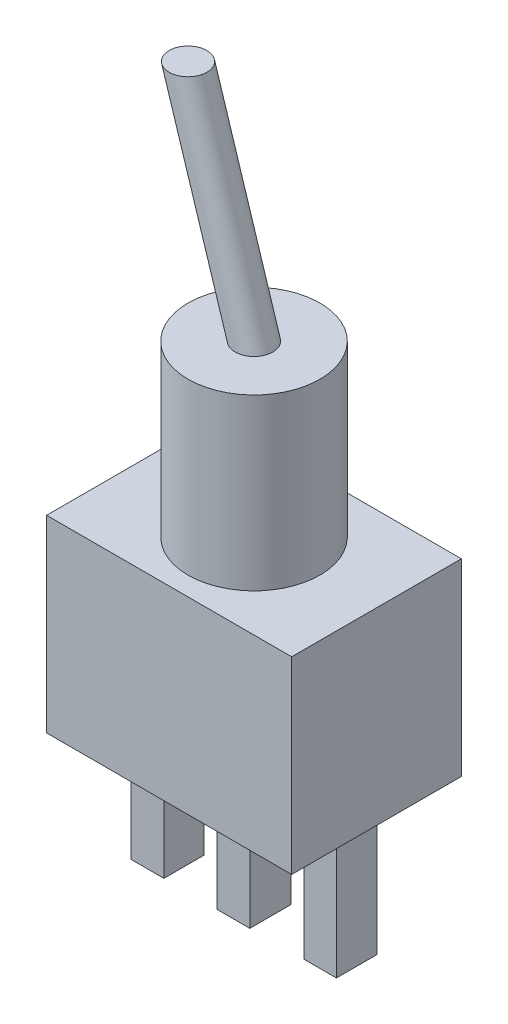
SolidWorks part; units mm, degrees
ref_plane "Front" through (0, 0, 0) normal (0, 0, 1) x (1, 0, 0)
ref_plane "Top" through (0, 0, 0) normal (0, 1, 0) x (1, 0, 0)
ref_plane "Right" through (0, 0, 0) normal (1, 0, 0) x (0, 0, -1)
sketch "草图1" plane through (0, 0, 0) normal (0, 1, 0) x (1, 0, 0)
  line L1 (-6.5, 4.5) -> (6.5, 4.5)
  line L2 (-6.5, 4.5) -> (-6.5, -4.5)
  line L3 (-6.5, -4.5) -> (6.5, -4.5)
  line L4 (6.5, 4.5) -> (6.5, -4.5)
  line L5 (-6.5, 4.5) -> (6.5, -4.5) construction
  line L6 (-6.5, -4.5) -> (6.5, 4.5) construction
  point P0 (0, 0)
  dimension "D1" = 13
  dimension "D2" = 9
extrude "凸台-拉伸1" add sketch "草图1" along normal blind 10
sketch "草图2" plane through (0, 10, 0) normal (0, 1, 0) x (1, 0, 0)
  circle A0 centre (0, 0) radius 3.5
extrude "凸台-拉伸2" add sketch "草图2" along normal blind 9
sketch "草图3" plane through (0, 0, 0) normal (0, 0, 1) x (1, 0, 0)
  line L0 (0, 19) -> (-3.5, 30.1002)
  line L1 (3.5, 19) -> (-3.5, 19) construction
sketch "草图4" plane through (0, 19, 0) normal (0, 1, 0) x (1, 0, 0)
  circle A0 centre (0, 0) radius 1
sweep "扫描1" add profiles "草图4" path "草图3"
sketch "草图5" plane through (0, 0, 0) normal (0, -1, 0) x (-1, 0, 0)
  line L0 (0, -2.9265) -> (0, 3.354) construction
  line L1 (-3.7101, -1.0698) -> (-5.4432, -1.0698)
  line L2 (-3.7101, -1.0698) -> (-3.7101, 1.0698)
  line L3 (-3.7101, 1.0698) -> (-5.4432, 1.0698)
  line L4 (-5.4432, -1.0698) -> (-5.4432, 1.0698)
  line L5 (-3.7101, -1.0698) -> (-5.4432, 1.0698) construction
  line L6 (-3.7101, 1.0698) -> (-5.4432, -1.0698) construction
  line L7 (3.7101, 1.0698) -> (5.4432, 1.0698)
  line L8 (5.4432, -1.0698) -> (5.4432, 1.0698)
  line L9 (3.7101, -1.0698) -> (5.4432, -1.0698)
  line L10 (3.7101, -1.0698) -> (3.7101, 1.0698)
  line L12 (0.8647, -1.0874) -> (-0.8647, -1.0874)
  line L13 (0.8647, -1.0874) -> (0.8647, 1.0874)
  line L14 (0.8647, 1.0874) -> (-0.8647, 1.0874)
  line L15 (-0.8647, -1.0874) -> (-0.8647, 1.0874)
  line L16 (0.8647, -1.0874) -> (-0.8647, 1.0874) construction
  line L17 (0.8647, 1.0874) -> (-0.8647, -1.0874) construction
  point P0 (-4.5766, 0)
  point P12 (0, 0)
  point P17 (5.2229, 1.2969)
  point P18 (0.8647, 1.0874)
  point P19 (3.7101, 0)
  point P20 (5.5884, 1.1735)
  point P21 (5.4432, 1.0698)
extrude "凸台-拉伸3" add sketch "草图5" along normal blind 7
